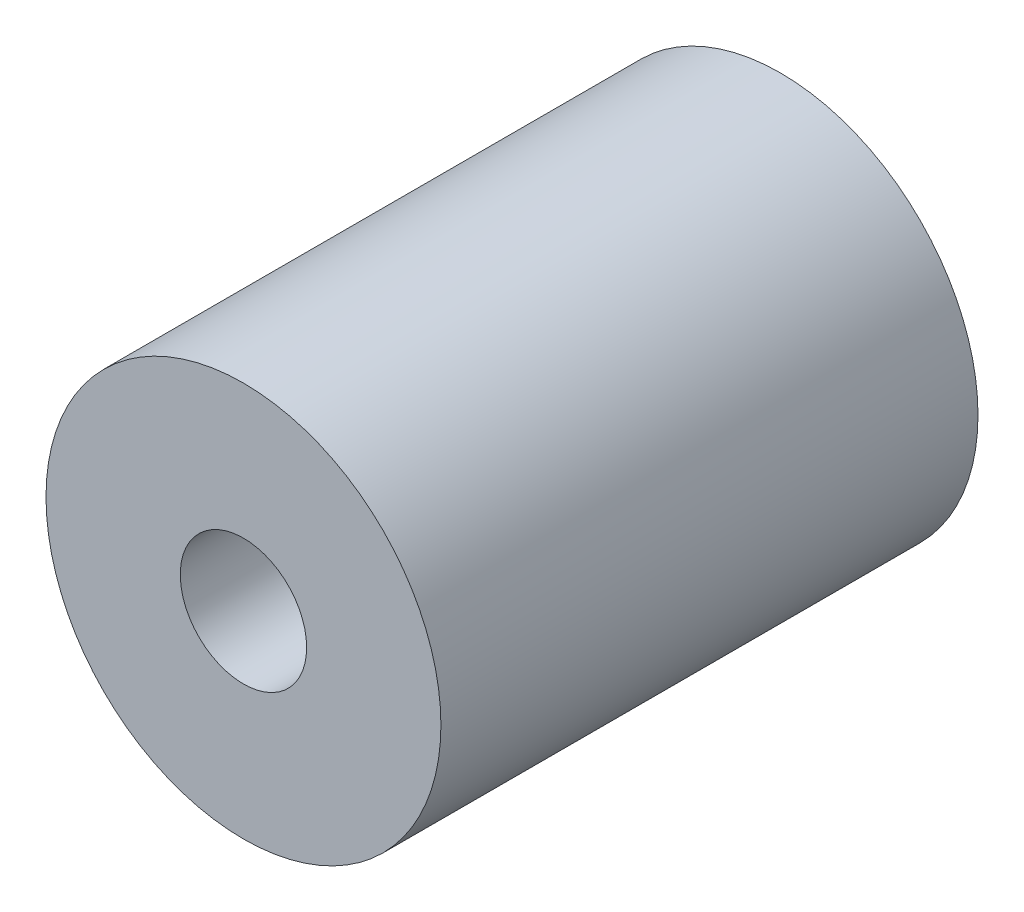
SolidWorks part; units mm, degrees
material "3.3535 (EN-AW 5754)"
ref_plane "Ebene vorne" through (0, 0, 0) normal (0, 0, 1) x (1, 0, 0)
ref_plane "Ebene oben" through (0, 0, 0) normal (0, 1, 0) x (1, 0, 0)
ref_plane "Ebene rechts" through (0, 0, 0) normal (1, 0, 0) x (0, 0, -1)
sketch "Skizze1" plane through (0, 0, 0) normal (0, 0, 1) x (1, 0, 0)
  circle A0 centre (0, 0) radius 12.5
  dimension "D1" = 25
extrude "Aufsatz-Linear austragen1" add sketch "Skizze1" along normal blind 34
sketch "Skizze2" plane through (0, 0, 34) normal (0, 0, 1) x (1, 0, 0)
  circle A0 centre (0, 0) radius 4
  dimension "D1" = 8
extrude "Schnitt-Linear austragen1" cut sketch "Skizze2" against normal blind 12
sketch "Skizze3" plane through (0, 0, 0) normal (0, 0, -1) x (-1, 0, 0)
  circle A0 centre (0, 0) radius 5
  dimension "D1" = 10
extrude "Schnitt-Linear austragen2" cut sketch "Skizze3" against normal blind 12
